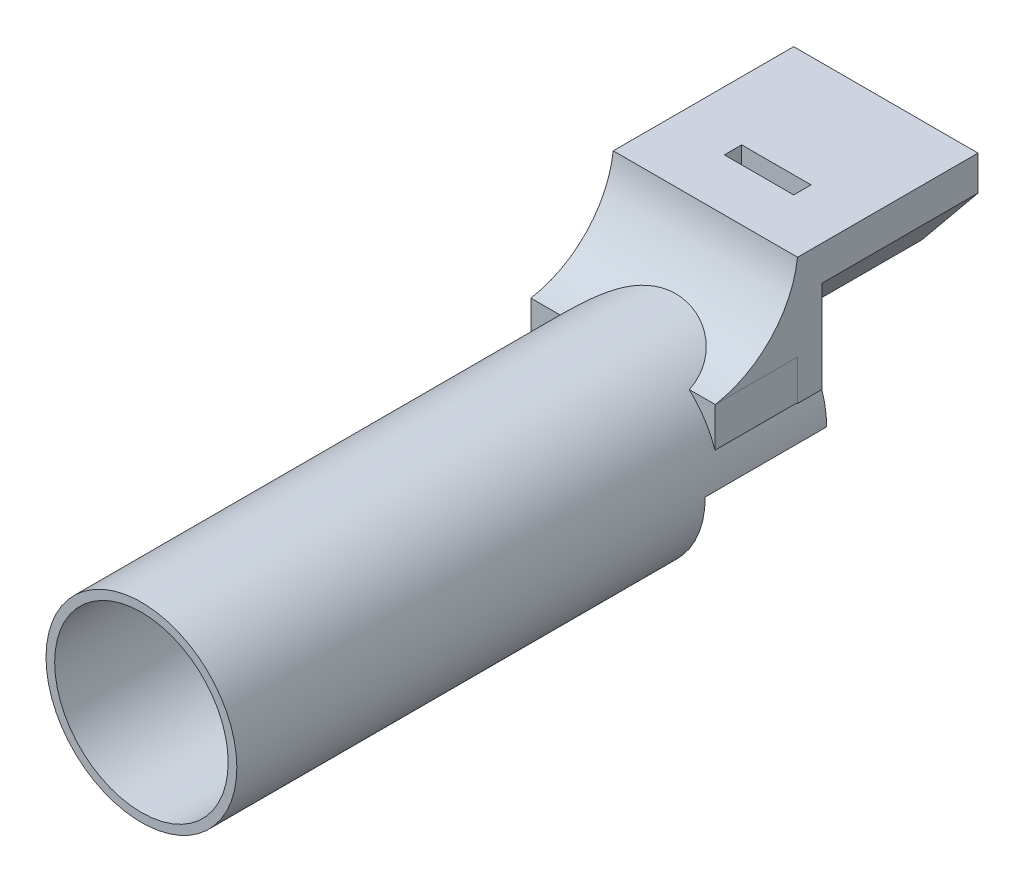
SolidWorks part; units mm, degrees
ref_plane "Front" through (0, 0, 0) normal (0, 0, 1) x (1, 0, 0)
ref_plane "Top" through (0, 0, 0) normal (0, 1, 0) x (1, 0, 0)
ref_plane "Right" through (0, 0, 0) normal (1, 0, 0) x (0, 0, -1)
sketch "Sketch1" plane through (0, 0, 0) normal (0, 0, 1) x (1, 0, 0)
  circle A0 centre (0, 0) radius 25
  circle A1 centre (0, 0) radius 27.5
  dimension "D1" = 50
  dimension "D2" = 55
extrude "Boss-Extrude1" add sketch "Sketch1" along normal blind 170
sketch "Sketch2" plane through (0, 0, 0) normal (0, 0, -1) x (-1, 0, 0)
  line L0 (-23.6854, 8) -> (23.6854, 8) construction
  line L2 (-33.6854, 11.5) -> (-13.6854, 11.5)
  line L3 (-33.6854, 11.5) -> (-33.6854, 4.5)
  line L4 (-33.6854, 4.5) -> (-13.6854, 4.5)
  line L5 (-13.6854, 11.5) -> (-13.6854, 4.5)
  line L6 (-33.6854, 11.5) -> (-13.6854, 4.5) construction
  line L7 (-33.6854, 4.5) -> (-13.6854, 11.5) construction
  line L8 (13.6854, 11.5) -> (33.6854, 11.5)
  line L9 (13.6854, 11.5) -> (13.6854, 4.5)
  line L10 (13.6854, 4.5) -> (33.6854, 4.5)
  line L11 (33.6854, 11.5) -> (33.6854, 4.5)
  line L12 (13.6854, 11.5) -> (33.6854, 4.5) construction
  line L13 (13.6854, 4.5) -> (33.6854, 11.5) construction
  circle A0 centre (0, 0) radius 4.5 construction
  circle A1 centre (0, 0) radius 25 construction
  circle A2 centre (0, 0) radius 26
  dimension "D1" = 9
  dimension "D5" = 10
  dimension "D6" = 10
  dimension "D7" = 52
  dimension "D2" = 8
  dimension "D3" = 7
  dimension "D4" = 7
ref_plane "Plane1" through (0, 0, 50) normal (0, 0, -1) x (-1, 0, 0)
sketch "Sketch5" plane through (0, 0, 50) normal (0, 0, -1) x (-1, 0, 0)
  circle A0 centre (0, 0) radius 15.5
  circle A1 centre (0, 0) radius 25
  dimension "D1" = 50
  dimension "D2" = 31
extrude "Boss-Extrude5" add sketch "Sketch5" against normal blind 80
sketch "Sketch7" plane through (0, 0, 0) normal (0, 1, 0) x (1, 0, 0)
  line L1 (-15, 0) -> (15, 0)
  line L2 (-15, 0) -> (-15, -10)
  line L3 (-15, -10) -> (15, -10)
  line L4 (15, 0) -> (15, -10)
  point P4 (0, 0)
  dimension "D1" = 30
  dimension "D2" = 10
extrude "Cut-Extrude3" cut sketch "Sketch7" against normal up to next
ref_plane "Plane2" through (0, -20, 0) normal (0, -1, 0) x (-1, 0, 0)
sketch "Sketch9" plane through (0, -20, 0) normal (0, -1, 0) x (-1, 0, 0)
  line L0 (-15, 0) -> (15, 0) construction
  line L1 (-13, 0) -> (-15, 0)
  line L2 (-13, 0) -> (-13, -10)
  line L3 (-13, -10) -> (-15, -10)
  line L4 (-15, 0) -> (-15, -10)
  line L5 (15, 0) -> (13, 0)
  line L6 (15, 0) -> (15, -10)
  line L7 (15, -10) -> (13, -10)
  line L8 (13, 0) -> (13, -10)
  point P8 (0, 0)
  dimension "D1" = 30
  dimension "D2" = 26
  dimension "D3" = 10
extrude "Boss-Extrude6" add sketch "Sketch9" along normal blind 5
ref_plane "Plane4" through (0, -25, 0) normal (0, -1, 0) x (-1, 0, 0)
sketch "Sketch10" plane through (0, -25, 0) normal (0, -1, 0) x (-1, 0, 0)
  line L1 (-15, 0) -> (15, 0)
  line L2 (-15, 0) -> (-15, -10)
  line L3 (-15, -10) -> (15, -10)
  line L4 (15, 0) -> (15, -10)
extrude "Boss-Extrude7" add sketch "Sketch10" along normal blind 3
sketch "Sketch11" plane through (0, -28, 0) normal (0, -1, 0) x (-1, 0, 0)
  line L0 (-10, -2) -> (10, -2) construction
  line L1 (15, 0) -> (-15, 0) construction
  circle A0 centre (-10, -2) radius 1.5
  circle A1 centre (10, -2) radius 1.5
  point P4 (0, -2)
  dimension "D2" = 3
  dimension "D1" = 2
  dimension "D3" = 20
extrude "Cut-Extrude4" cut sketch "Sketch11" against normal up to next
ref_plane "Plane5" through (0, 0, 120) normal (0, 0, -1) x (-1, 0, 0)
ref_plane "Plane8" through (0, 20, 0) normal (0, 1, 0) x (1, 0, 0)
sketch "草图2" plane through (0, 0, 0) normal (0, 0, -1) x (-1, 0, 0)
  line L1 (-26.1074, 45.1492) -> (27.0136, 45.1492)
  line L2 (-26.1074, 45.1492) -> (-26.1074, 5.1492)
  line L3 (-26.1074, 5.1492) -> (27.0136, 5.1492)
  line L4 (27.0136, 45.1492) -> (27.0136, 5.1492)
  line L5 (-26.1074, 45.1492) -> (27.0136, 5.1492) construction
  line L6 (-26.1074, 5.1492) -> (27.0136, 45.1492) construction
  arc A0 (15, -23.0489) -> (-15, -23.0489) centre (0, 0) ccw construction
  point P0 (0.4531, 25.1492)
  arc M9 (15, -23.0489) -> (-15, -23.0489) centre (0, 0) ccw
extrude "凸台-拉伸2" add sketch "草图2" against normal blind 7 contours L4 L1 L2 M9
ref_plane "base level 1" through (0, 0, 35) normal (0, 0, 1) x (1, 0, 0)
sketch "草图9" plane through (0, 0, 35) normal (0, 0, 1) x (1, 0, 0)
  line L1 (80.918, 0) -> (-80.8455, 0)
  line L2 (80.918, 0) -> (80.918, -49.9918)
  line L3 (80.918, -49.9918) -> (-80.8455, -49.9918)
  line L4 (-80.8455, 0) -> (-80.8455, -49.9918)
extrude "切除-拉伸2" cut sketch "草图9" against normal blind 35
sketch "草图10" plane through (0, 0, 0) normal (0, 0, -1) x (-1, 0, 0)
  line L0 (27.0136, 45.1492) -> (27.0136, 5.1492) construction
  line L1 (-26.1074, 45.1492) -> (27.0136, 45.1492)
  line L2 (-26.1074, 45.1492) -> (-26.1074, 35.1492)
  line L3 (-26.1074, 35.1492) -> (27.0136, 35.1492)
  line L4 (27.0136, 45.1492) -> (27.0136, 35.1492)
  dimension "D1" = 10
extrude "凸台-拉伸3" add sketch "草图10" along normal blind 45 contours L2 L1 L4 L3
sketch "草图12" plane through (0, 35.1492, 0) normal (0, -1, 0) x (1, 0, 0)
  line L1 (10, -13) -> (-10, -13)
  line L2 (10, -13) -> (10, -8)
  line L3 (10, -8) -> (-10, -8)
  line L4 (-10, -13) -> (-10, -8)
  line L5 (10, -13) -> (-10, -8) construction
  line L6 (10, -8) -> (-10, -13) construction
  point P0 (0, -10.5)
  point P5 (-94.524, -14.5284)
  point P6 (0, 0)
  point P7 (0, 0)
  point P8 (0, 0)
  point P9 (0, 0)
  point P10 (0, 0)
  point P11 (0, 0)
  point P12 (0, 0)
  point P13 (0, 0)
  point P14 (0, 0)
  point P15 (0, 0)
  point P16 (0, 0)
extrude "切除-拉伸3" cut sketch "草图12" against normal up to next
sketch "草图16" plane through (0, 0, 50) normal (0, 0, -1) x (-1, 0, 0)
  line L0 (19.3384, 15.8438) -> (-19.7422, 15.3377)
  arc A0 (19.3384, 15.8438) -> (-19.7422, 15.3377) centre (0, 0) ccw
  circle A1 centre (0, 0) radius 25 construction
extrude "凸台-拉伸4" add sketch "草图16" along normal blind 50 contours L0 A0
sketch "草图18" plane through (-27.0136, 0, 0) normal (-1, 0, 0) x (0, 0, 1)
  line L0 (7, 45.1492) -> (7, 20.2491)
  line L1 (7, 45.1492) -> (7, 5.1492) construction
  line L2 (7, 20.2491) -> (30.7333, 20.2491)
  arc A0 (7, 45.1492) -> (30.7333, 20.2491) centre (35.5628, 48.613) ccw
extrude "凸台-拉伸5" add sketch "草图18" against normal up to surface (53.121 mm away) contours L2 A0 L0
sketch "草图21" plane through (0, 0, 7) normal (0, 0, 1) x (1, 0, 0)
  line L0 (26.1074, 20.2491) -> (26.0452, 8.8259)
  line L1 (33.6854, 11.5) -> (13.6854, 4.5) construction
  line L2 (26.0452, 8.8259) -> (18.6071, 20.2491)
  line L3 (18.6071, 20.2491) -> (26.1074, 20.2491)
  circle A0 centre (0, 0) radius 27.5 construction
extrude "凸台-拉伸7" add sketch "草图21" along normal blind 23.733 contours L3 L0 L2
sketch "草图23" plane through (0, 0, 7) normal (0, 0, 1) x (1, 0, 0)
  line L0 (-18.6071, 20.2491) -> (-27.0136, 5.1492)
  line L1 (-27.0136, 5.1492) -> (-27.0136, 20.2491)
  line L2 (-27.0136, 45.1492) -> (-27.0136, 20.2491) construction
  line L3 (-27.0136, 20.2491) -> (-27.0136, 5.1492) construction
  line L4 (-27.0136, 20.2491) -> (-18.6071, 20.2491)
extrude "凸台-拉伸8" add sketch "草图23" along normal blind 23.733 contours L4 L0 L1
sketch "草图24" plane through (0, 0, 0) normal (0, 0, -1) x (-1, 0, 0)
  line L0 (-26.1074, 35.1492) -> (-10, 35.1492)
  line L1 (-26.1074, 35.1492) -> (27.0136, 35.1492) construction
  line L2 (-10, 35.1492) -> (-10, 15.4638)
  line L3 (19.3384, 15.8438) -> (-19.7422, 15.3377) construction
  line L5 (27.0136, 35.1492) -> (10, 35.1492)
  line L6 (10, 35.1492) -> (10, 15.7229)
  line L7 (-26.1074, 35.1492) -> (-10, 15.4638)
  line L8 (10, 15.7229) -> (27.0136, 35.1492)
extrude "凸台-拉伸11" add sketch "草图24" along normal up to surface (45 mm away) contours L8 L5 L6 | L7 L2 L0 up to face at (-0.4531, 40.1492, -45)
